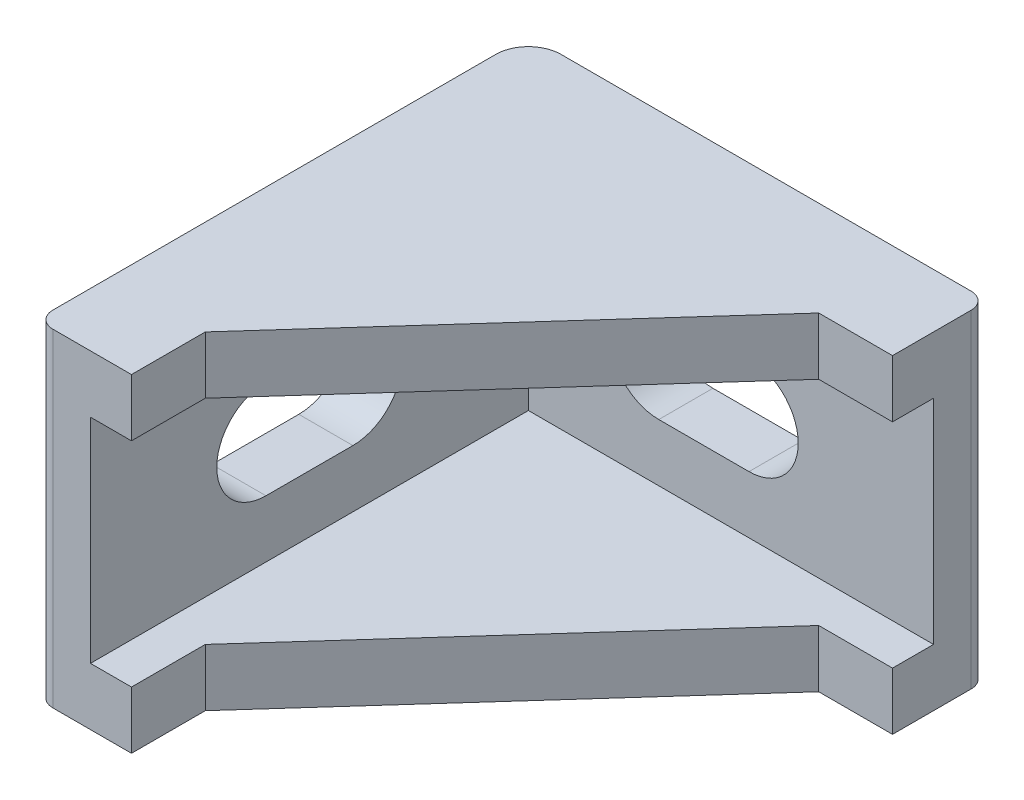
SolidWorks part; units mm, degrees
ref_plane "Front Plane" through (0, 0, 0) normal (0, 0, 1) x (1, 0, 0)
ref_plane "Top Plane" through (0, 0, 0) normal (0, 1, 0) x (1, 0, 0)
ref_plane "Right Plane" through (0, 0, 0) normal (1, 0, 0) x (0, 0, -1)
sketch "Sketch1" plane through (0, 0, 0) normal (0, 0, 1) x (1, 0, 0)
  line L0 (11.25, 10) -> (16.75, 10) construction
  line L1 (0, 0) -> (28, 0)
  line L2 (0, 0) -> (0, 20)
  line L3 (0, 20) -> (28, 20)
  line L4 (28, 0) -> (28, 20)
  line L5 (11.25, 13) -> (16.75, 13)
  line L6 (11.25, 7) -> (16.75, 7)
  arc A0 (11.25, 13) -> (11.25, 7) centre (11.25, 10) ccw
  arc A1 (16.75, 7) -> (16.75, 13) centre (16.75, 10) ccw
  point P7 (14, 10)
  point P12 (8.25, 10)
  point P13 (19.75, 10)
  dimension "D1" = 28
  dimension "D2" = 20
  dimension "D3" = 6
  dimension "D4" = 11.5
  dimension "D5" = 10
  dimension "D6" = 14
extrude "Boss-Extrude1" add sketch "Sketch1" along normal blind 3.3
sketch "Sketch2" plane through (0, 0, 3.3) normal (0, 0, 1) x (1, 0, 0)
  line L0 (0, 0) -> (28, 0) construction
  line L1 (0, 20) -> (3.3, 20)
  line L2 (0, 20) -> (0, 0)
  line L3 (0, 0) -> (3.3, 0)
  line L4 (3.3, 20) -> (3.3, 0)
  dimension "D1" = 3.3
extrude "Boss-Extrude2" add sketch "Sketch2" along normal blind 26.7
sketch "Sketch3" plane through (3.3, 0, 0) normal (1, 0, 0) x (0, 0, -1)
  line L0 (-19.3, 10) -> (-14, 10) construction
  line L1 (-19.3, 13) -> (-14, 13)
  line L2 (-19.3, 7) -> (-14, 7)
  line L3 (-30, 20) -> (-3.3, 20) construction
  line L4 (-30, 0) -> (-30, 20) construction
  arc A0 (-19.3, 13) -> (-19.3, 7) centre (-19.3, 10) ccw
  arc A1 (-14, 7) -> (-14, 13) centre (-14, 10) ccw
  point P2 (-16.65, 10)
  point P9 (-11, 10)
  point P10 (-22.3, 10)
  dimension "D1" = 10
  dimension "D2" = 11.3
  dimension "D3" = 13.35
  dimension "D4" = 6
extrude "Cut-Extrude1" cut sketch "Sketch3" against normal through all
sketch "Sketch4" plane through (0, 0, 0) normal (0, -1, 0) x (1, 0, 0)
  line L0 (3.3, 30) -> (5.8, 30)
  line L1 (5.8, 30) -> (5.8, 25.5)
  line L2 (5.8, 25.5) -> (23.5, 5.8)
  line L3 (28, 3.3) -> (28, 5.8)
  line L4 (3.3, 3.3) -> (28, 3.3) construction
  line L5 (28, 3.3) -> (28, 0) construction
  line L6 (28, 5.8) -> (23.5, 5.8)
  line L7 (3.3, 30) -> (3.3, 3.3)
  line L8 (3.3, 3.3) -> (28, 3.3)
  dimension "D1" = 2.5
  dimension "D2" = 2.5
  dimension "D3" = 4.5
  dimension "D4" = 4.5
extrude "Boss-Extrude3" add sketch "Sketch4" against normal blind 3.5
sketch "Sketch5" plane through (0, 20, 0) normal (0, 1, 0) x (1, 0, 0)
  line L0 (28, -3.3) -> (28, -5.8)
  line L1 (28, -5.8) -> (23.5, -5.8)
  line L2 (23.5, -5.8) -> (5.8, -25.5)
  line L3 (5.8, -25.5) -> (5.8, -30)
  line L4 (5.8, -30) -> (3.3, -30)
  line L5 (3.3, -30) -> (3.3, -3.3)
  line L6 (3.3, -3.3) -> (28, -3.3)
extrude "Boss-Extrude4" add sketch "Sketch5" against normal blind 3.5
fillet "Fillet1" radius 2 1 edges at (0, 10, 0)
fillet "Fillet2" radius 1 1 edges at (0, 10, 30)
fillet "Fillet3" radius 1 1 edges at (28, 10, 0)
